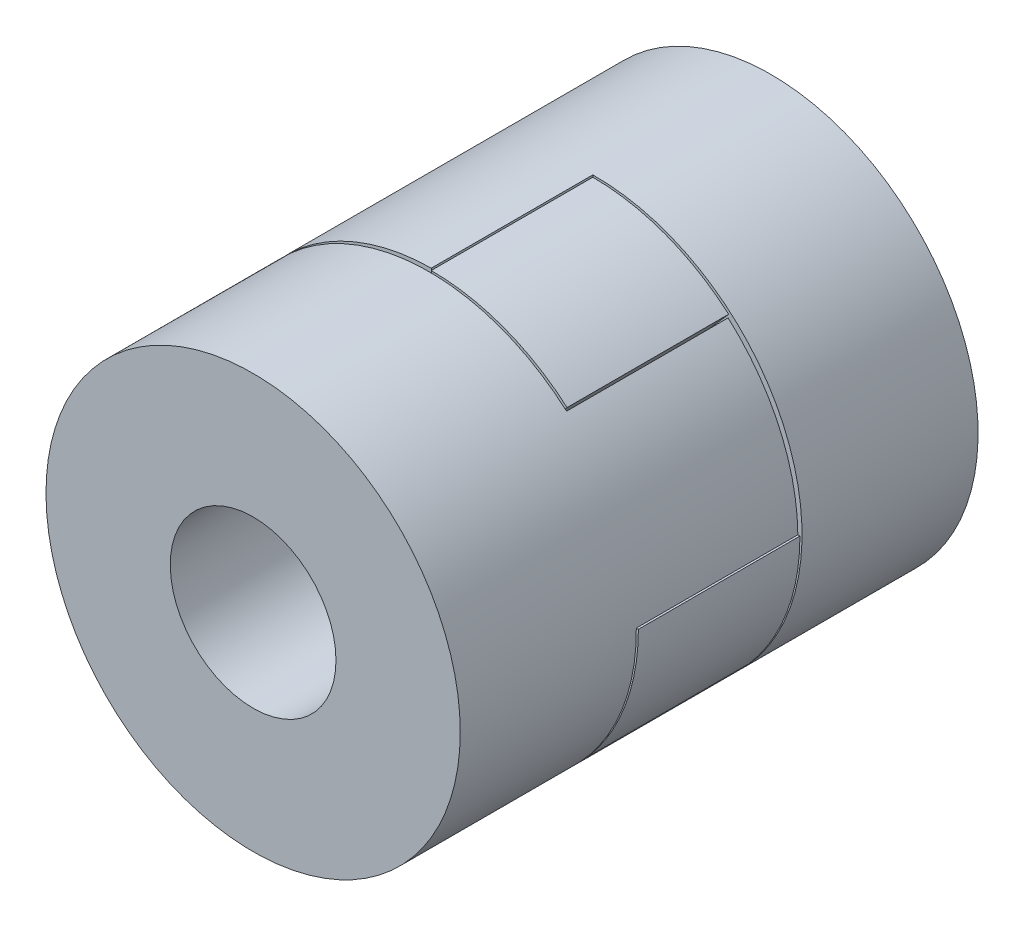
SolidWorks part; units mm, degrees
ref_plane "Front Plane" through (0, 0, 0) normal (0, 0, 1) x (1, 0, 0)
ref_plane "Top Plane" through (0, 0, 0) normal (0, 1, 0) x (1, 0, 0)
ref_plane "Right Plane" through (0, 0, 0) normal (1, 0, 0) x (0, 0, -1)
sketch "Sketch1" plane through (0, 0, 0) normal (0, 0, 1) x (1, 0, 0)
  line L0 (0, 10) -> (6.5572, 7.55) construction
  line L1 (0, 10) -> (0, 0)
  line L2 (0, 0) -> (10, 0) construction
  line L3 (6.5572, 7.55) -> (0, 0)
  line L4 (10, 0) -> (0, 0)
  line L5 (7.55, -6.5572) -> (0, 0)
  line L6 (0, -10) -> (0, 0)
  line L7 (-6.5572, -7.55) -> (0, 0)
  line L8 (-10, 0) -> (0, 0)
  line L9 (-7.55, 6.5572) -> (0, 0)
  arc A1 (0, 10) -> (6.5572, 7.55) centre (0, 0) cw
  arc A2 (6.5572, 7.55) -> (10, 0) centre (0, 0) cw construction
  arc A3 (10, 0) -> (7.55, -6.5572) centre (0, 0) cw
  arc A4 (7.55, -6.5572) -> (0, -10) centre (0, 0) cw construction
  arc A5 (0, -10) -> (-6.5572, -7.55) centre (0, 0) cw
  arc A6 (-6.5572, -7.55) -> (-10, 0) centre (0, 0) cw construction
  arc A7 (-10, 0) -> (-7.55, 6.5572) centre (0, 0) cw
  arc A8 (-7.55, 6.5572) -> (0, 10) centre (0, 0) cw construction
  point P6 (0, 0)
  dimension "D2" = 20
  dimension "D1" = 7
  dimension "D3" = 4
extrude "Boss-Extrude1" add sketch "Sketch1" along normal mid plane 7.8 contours A1 L1 L3 | A3 L4 L5 | A5 L6 L7 | A7 L8 L9
ref_plane "Plane1" through (0, 0, 4) normal (0, 0, 1) x (1, 0, 0)
sketch "Sketch2" plane through (0, 0, 4) normal (0, 0, 1) x (1, 0, 0)
  circle A0 centre (0, 0) radius 10
  arc A1 (10, 0) -> (6.5572, 7.55) centre (0, 0) ccw construction
  circle A2 centre (0, 0) radius 4
  point P8 (0, 0)
  dimension "D1" = 8
extrude "Boss-Extrude2" add sketch "Sketch2" along normal blind 8.5 separate body
sketch "Sketch3" plane through (0, 0, 4) normal (0, 0, -1) x (-1, 0, 0)
  line L0 (-6.5572, 7.55) -> (0, 0) construction
  line L1 (0, 0) -> (-10, 0) construction
  line L2 (-6.6324, 7.4841) -> (-0.2193, 0.1)
  line L3 (-0.2193, 0.1) -> (-9.9995, 0.1)
  line L4 (-0.2193, 0.1) -> (-0.1438, 0.1656) construction
  line L5 (-0.2193, 0.1) -> (-0.2193, 0) construction
  line L6 (-4.1489, -9.0987) -> (4.1489, 9.0987) construction
  line L7 (-0.2193, 0.1) -> (0, 0) construction
  line L8 (9.9995, -0.1) -> (0.2193, -0.1)
  line L9 (0.2193, -0.1) -> (6.6324, -7.4841)
  arc A0 (-6.5572, 7.55) -> (-6.6324, 7.4841) centre (0, 0) ccw construction
  circle A1 centre (0, 0) radius 10 construction
  arc A2 (-6.6324, 7.4841) -> (-9.9995, 0.1) centre (0, 0) ccw
  arc A3 (-9.9995, 0.1) -> (-10, 0) centre (0, 0) ccw construction
  arc A4 (7.55, 6.5572) -> (0, 10) centre (0, 0) ccw construction
  arc A5 (9.9995, -0.1) -> (6.6324, -7.4841) centre (0, 0) cw
  point P16 (0, 0)
  dimension "D1" = 0.1
extrude "Boss-Extrude3" add sketch "Sketch3" along normal blind 7.8
ref_plane "Plane2" through (0, 0, -4) normal (0, 0, -1) x (-1, 0, 0)
sketch "Sketch4" plane through (0, 0, -4) normal (0, 0, -1) x (-1, 0, 0)
  circle A0 centre (0, 0) radius 10
  arc A1 (-7.55, -6.5572) -> (0, -10) centre (0, 0) ccw construction
  circle A2 centre (0, 0) radius 2.5
  dimension "D1" = 5
extrude "Boss-Extrude5" add sketch "Sketch4" along normal blind 8.5 separate body
sketch "Sketch5" plane through (0, 0, -4) normal (0, 0, 1) x (1, 0, 0)
  line L0 (7.55, -6.5572) -> (0, 0) construction
  line L1 (0, 0) -> (0, -10) construction
  line L2 (0, 0) -> (0.1, -0.2193) construction
  line L3 (0.1, -0.2193) -> (7.4841, -6.6324)
  line L4 (0.1, -0.2193) -> (0.1, -9.9995)
  line L5 (-9.0987, -4.1489) -> (9.0987, 4.1489) construction
  line L6 (0, -0.2193) -> (0.1, -0.2193) construction
  line L7 (0.1656, -0.1438) -> (0.1, -0.2193) construction
  line L8 (-0.1, 0.2193) -> (-7.4841, 6.6324)
  line L9 (-0.1, 0.2193) -> (-0.1, 9.9995)
  arc A0 (7.55, -6.5572) -> (7.4841, -6.6324) centre (0, 0) cw construction
  arc A1 (7.4841, -6.6324) -> (0.1, -9.9995) centre (0, 0) cw
  arc A2 (0.1, -9.9995) -> (0, -10) centre (0, 0) cw construction
  arc A3 (10, 0) -> (6.5572, 7.55) centre (0, 0) ccw construction
  arc A4 (-0.1, 9.9995) -> (-7.4841, 6.6324) centre (0, 0) ccw
  point P13 (0, 0)
  dimension "D1" = 0.1
extrude "Boss-Extrude6" add sketch "Sketch5" along normal blind 7.8
